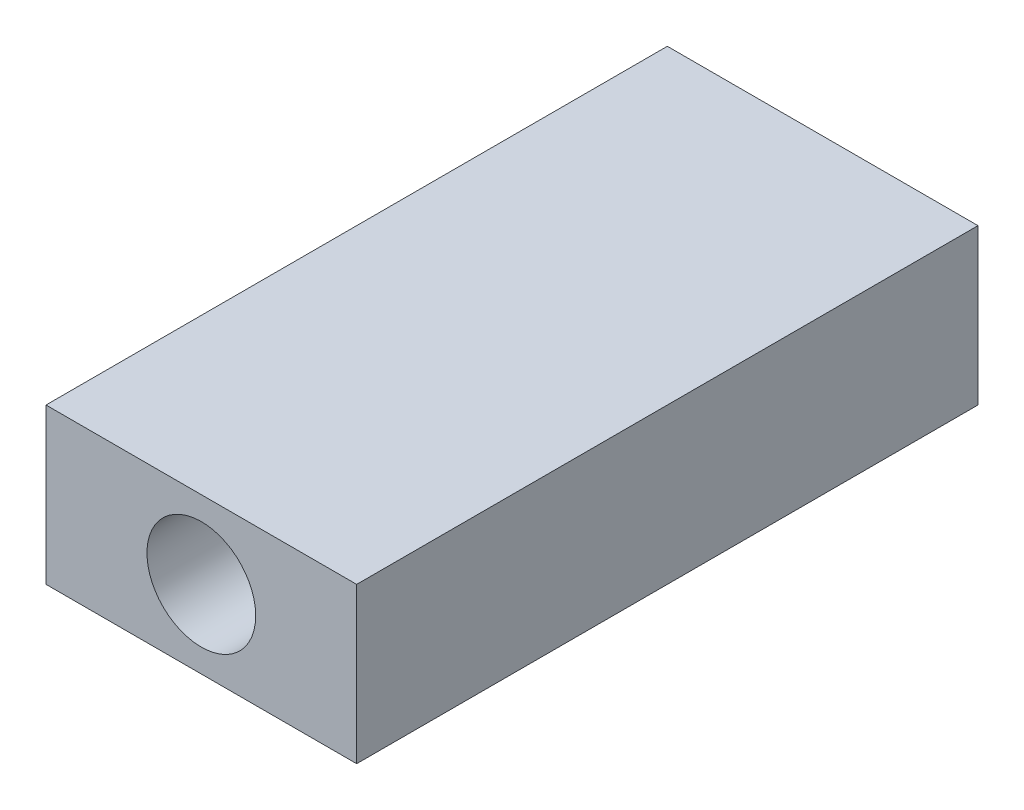
SolidWorks part; units mm, degrees
ref_plane "Front" through (0, 0, 0) normal (0, 0, 1) x (1, 0, 0)
ref_plane "Top" through (0, 0, 0) normal (0, 1, 0) x (1, 0, 0)
ref_plane "Right" through (0, 0, 0) normal (1, 0, 0) x (0, 0, -1)
sketch "Sketch1" plane through (0, 0, 0) normal (0, 0, 1) x (1, 0, 0)
  line L1 (-10, 17.025) -> (10, 17.025)
  line L2 (-10, 17.025) -> (-10, 27.025)
  line L3 (-10, 27.025) -> (10, 27.025)
  line L4 (10, 17.025) -> (10, 27.025)
  line L5 (-10, 17.025) -> (10, 27.025) construction
  line L6 (-10, 27.025) -> (10, 17.025) construction
  circle A0 centre (0, 22.025) radius 3.5
  circle A2 centre (0, 22.025) radius 3.5 construction
  circle A4 centre (0, 22.025) radius 3.5 construction
  point P0 (0, 23.1347)
  point P6 (0, 22.025)
  dimension "D1" = 7
  dimension "D2" = 10
  dimension "D3" = 20
extrude "Boss-Extrude1" add sketch "Sketch1" along normal blind 40
